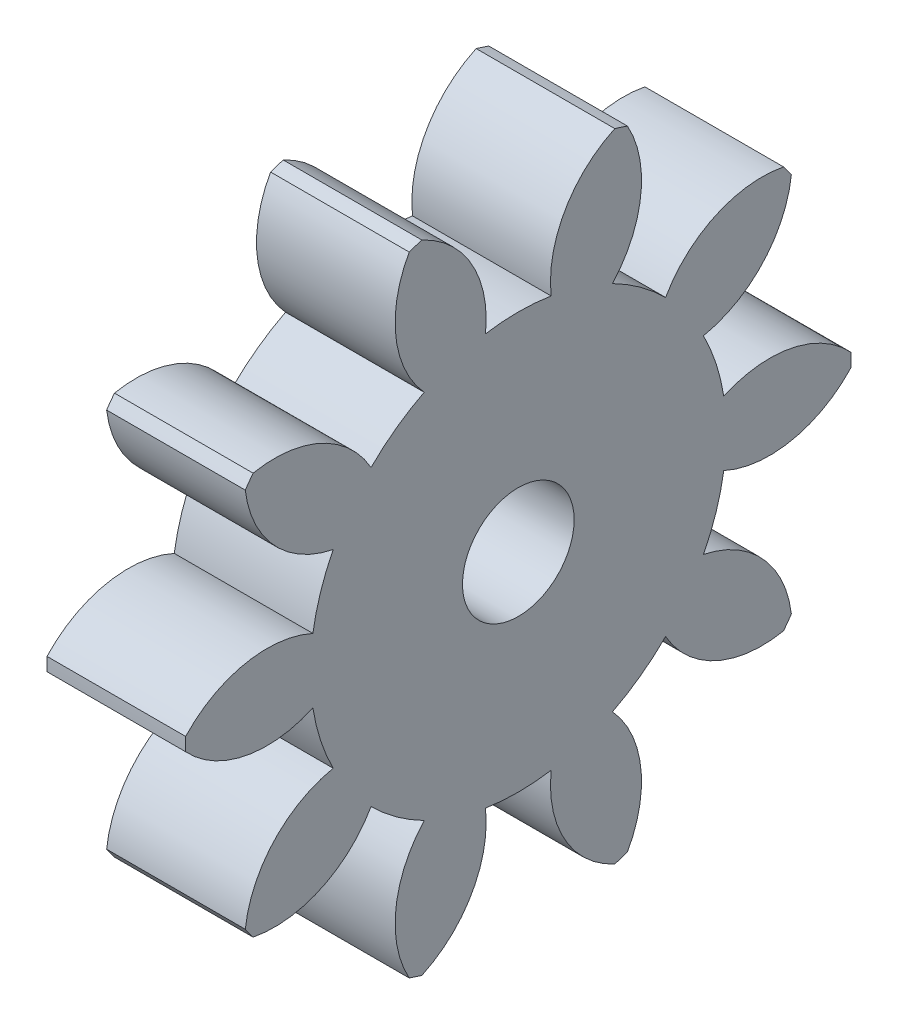
SolidWorks part; units mm, degrees
ref_plane "Plane1" through (0, 0, 0) normal (0, 0, 1) x (1, 0, 0)
ref_plane "Plane2" through (0, 0, 0) normal (0, 1, 0) x (1, 0, 0)
ref_plane "Plane3" through (0, 0, 0) normal (1, 0, 0) x (0, 0, -1)
other "Configuration Table"
sketch "HoldingSke" plane through (0, 0, 0) normal (0, 1, 0) x (1, 0, 0)
  line L0 (0, 0) -> (125.0706, -22.0533)
  line L1 (-15, 0) -> (100, 0) construction
  line L2 (0, 0) -> (-2.1039, 2.3779)
  line L3 (0, 0) -> (-11.863, 4.5341)
  line L4 (0, 0) -> (8.5048, 1.4996)
  line L5 (0, 0) -> (-47.5972, -17.7524)
  line L6 (0, 0) -> (-10.5278, -7.1032)
  line L7 (-2.1039, 2.3779) -> (8.8308, 51.9871)
  line L8 (-76.2, 54.61) -> (-75.184, 54.61)
  line L9 (-71.009, 38.7566) -> (-53.1078, 45.2721)
  line L10 (-76.2, 71.12) -> (104.1128, 71.12)
  line L11 (0, 0) -> (-12.7, 0)
  line L12 (-76.2, 101.6) -> (-76.0095, 101.6)
  line L13 (24.9733, 27.94) -> (52.9518, 28.4284)
  line L14 (24.9733, 27.94) -> (24.9746, 27.94)
  line L15 (24.9733, 27.94) -> (100.4006, 29.5858)
  circle A0 centre (0, 0) radius 0.3969
  circle A1 centre (0, 0) radius 19.0487
  circle A2 centre (0, 0) radius 38.1
  circle A3 centre (0, 0) radius 0.3969
  dimension "MHD" = 38.0975
  dimension "Hub_dia" = 76.2
  dimension "Bore" = 0.7937
  dimension "MBD" = 0.7937
  dimension "Num_teeth" = 10
  dimension "Pitch" = 127
  dimension "Overall_len" = 50.8
  dimension "Show_teeth" = 10
  dimension "Thickness" = 12.7
  dimension "OAL" = 50.8001
  dimension "T_dim" = 1.016
  dimension "Ap" = 20
  dimension "H" = 19.05
  dimension "Pitch_radius" = 180.3128
  dimension "Width" = 12.7
  dimension "Backlash" = 0.1905
  dimension "Addendum_fac" = 1
  dimension "Dedendum_fac" = 1.25
  dimension "Clearance_fac" = 0.25
  dimension "Dedendum_add" = 0.0013
sketch "BasProSke" plane through (0, 0, 0) normal (0, 1, 0) x (1, 0, 0)
  line L0 (-10, 0) -> (60, 0) construction
  line L1 (0, 0) -> (0, 30.48)
  line L2 (0, 0) -> (12.7, 0)
  line L3 (12.7, 0) -> (12.7, 30.48)
  line L4 (12.7, 30.48) -> (0, 30.48)
  dimension "Thickness" = 12.7
  dimension "Diameter" = 60.96
revolve "Base-Revolve" add sketch "BasProSke" angle 360 about L0
sketch "TooCutSke" plane through (0, 0, 0) normal (1, 0, 0) x (0, 0, -1)
  line L1 (0, 0) -> (0, 107) construction
  line L2 (0, 0) -> (-4.3061, 25.0323) construction
  line L3 (0, 0) -> (-15.536, 47.815) construction
  line L4 (-4.3061, 25.0323) -> (-7.768, 23.9075) construction
  arc A0 (3.0076, 18.8098) -> (-3.0076, 18.8098) centre (0, 0) ccw
  arc A1 (8.8722, 29.1867) -> (-8.8722, 29.1867) centre (0, 0) ccw
  circle A2 centre (0, 0) radius 25.4 construction
  circle A3 centre (0, 0) radius 23.8682 construction
  arc A4 (-3.0076, 18.8098) -> (-8.8722, 29.1867) centre (-13.1034, 19.9497) ccw
  arc A5 (8.8722, 29.1867) -> (3.0076, 18.8098) centre (13.1034, 19.9497) ccw
  dimension "Root_dia" = 38.0975
  dimension "Overcut_dia" = 61.0108
  dimension "Pitch_dia" = 50.8
  dimension "Base_dia" = 47.7364
  dimension "Flank_rad" = 10.16
  dimension "Half_ang" = 18
  dimension "Half_CT" = 3.6401
extrude "ToothCut" cut sketch "TooCutSke" along normal through all
fillet "Breaks" [suppressed] radius 0.1016
fillet "RootFillets" [suppressed] radius 1.2713
pattern_circular "TeethCuts" count 10 every 36 about axis through (-10, 0, 0) along (1, 0, 0) of "ToothCut", "RootFillets", "Breaks"
sketch "HubNeaOneSke" plane through (0, 0, 0) normal (-1, 0, 0) x (0, 0, 1)
  circle A0 centre (0, 0) radius 19.0487
  dimension "Diameter" = 38.0975
extrude "HubNearOne" [suppressed] add sketch "HubNeaOneSke" along normal blind 38.1001
sketch "HubNeaBotSke" plane through (0, 0, 0) normal (-1, 0, 0) x (0, 0, 1)
  circle A0 centre (0, 0) radius 19.0487
  dimension "Diameter" = 38.0975
extrude "HubNearBoth" [suppressed] add sketch "HubNeaBotSke" along normal blind 19.05
ref_plane "FarPln" through (12.7, 0, 0) normal (1, 0, 0) x (0, 0, -1)
sketch "HubFarSke" plane through (12.7, 0, 0) normal (1, 0, 0) x (0, 0, -1)
  circle A0 centre (0, 0) radius 19.0487
  dimension "Diameter" = 38.0975
extrude "HubFar" [suppressed] add sketch "HubFarSke" along normal blind 19.05
sketch "BorSke" plane through (0, 0, 0) normal (1, 0, 0) x (0, 0, -1)
  circle A0 centre (0, 0) radius 0.3969
  dimension "Diameter" = 0.7937
extrude "Bore" cut sketch "BorSke" along normal mid plane 101.6001
sketch "KeySke" plane through (0, 0, 0) normal (1, 0, 0) x (0, 0, -1)
  line L0 (-0.127, 0) -> (-0.127, 0.6191)
  line L1 (-0.127, 0.6191) -> (0.127, 0.6191)
  line L2 (0.127, 0.6191) -> (0.127, 0)
  line L3 (0, 0) -> (0, 34) construction
  line L4 (-0.127, 0) -> (0.127, 0)
  dimension "Offset" = 0.6191
extrude "Keyway" [suppressed] cut sketch "KeySke" along normal mid plane 101.6001
pattern_circular "Keyway2" [suppressed] count 2 every 90 about axis through (-10, 0, 0) along (1, 0, 0)
sketch "Sketch1" plane through (12.7, 0, 0) normal (1, 0, 0) x (0, 0, -1)
  circle A0 centre (0, 0) radius 5.1137
extrude "Cut-Extrude1" cut sketch "Sketch1" against normal through all
equation "' \"Pitch@HoldingSke\" = 4"
equation "' \"Num_teeth@HoldingSke\" = 12"
equation "' \"Ap@HoldingSke\" =  20"
equation "' \"Ap@HoldingSke\" = 20"
equation "' \"Width@HoldingSke\" = 0.5"
equation "' \"Hub_dia@HoldingSke\"= 1"
equation "' \"Hub_dia@HoldingSke\" = 1"
equation "' \"Overall_len@HoldingSke\" = 1.0"
equation "' \"Bore@HoldingSke\" = 0.75"
equation "' \"T_dim@HoldingSke\" = 0.85"
equation "' \"Width@KeySke\" = 0.25"
equation "' \"Show_teeth@HoldingSke\" = 13"
equation "' \"Backlash@HoldingSke\" = 0.009"
equation "' \"Addendum_fac@HoldingSke\" = 1.0"
equation "' \"Dedendum_fac@HoldingSke\" = 1.25"
equation "' \"Dedendum_add@HoldingSke\" = 0.00005"
equation "' \"Clearance_fac@HoldingSke\" = 0.25"
equation "' \"Pitch@HoldingSke\" = 0.5"
equation "' \"Num_teeth@HoldingSke\" = 23"
equation "' \"Show_teeth@HoldingSke\" = 23"
equation "' \"Backlash@HoldingSke\" = 0.0375"
equation "\"Overcut_dia@TooCutSke\" = (\"Num_teeth@HoldingSke\" + 2 * \"Addendum_fac@HoldingSke\") / \"Pitch@HoldingSke\" + 0.002"
equation "\"Pitch_dia@TooCutSke\" = \"Num_teeth@HoldingSke\" / \"Pitch@HoldingSke\""
equation "\"Base_dia@TooCutSke\" = \"Num_teeth@HoldingSke\" / \"Pitch@HoldingSke\" * cos((\"Ap@HoldingSke\"  * 3.14159265 / 180))"
equation "\"Root_dia@TooCutSke\" = (\"Num_teeth@HoldingSke\" + 2) / \"Pitch@HoldingSke\" - 2 * (\"Addendum_fac@HoldingSke\" + \"Dedendum_fac@HoldingSke\") / \"Pitch@HoldingSke\" - \"Dedendum_add@HoldingSke\" * 2"
equation "\"Half_ang@TooCutSke\" = 180 / \"Num_teeth@HoldingSke\""
equation "\"Half_CT@TooCutSke\" = \"Num_teeth@HoldingSke\" / \"Pitch@HoldingSke\" * sin((3.14159265 / 2 / \"Num_teeth@HoldingSke\")) / 2 - 7 * \"Backlash@HoldingSke\" / 4"
equation "\"Flank_rad@TooCutSke\" = \"Num_teeth@HoldingSke\" / \"Pitch@HoldingSke\" / 5"
equation "\"Radius@RootFillets\" = \"Clearance_fac@HoldingSke\" / \"Pitch@HoldingSke\" + \"Dedendum_add@HoldingSke\""
equation "\"Break_rad@Breaks\" = 0.02 / \"Pitch@HoldingSke\""
equation "\"Thickness@HoldingSke\" = \"Width@HoldingSke\""
equation "\"OAL@HoldingSke\" = \"Thickness@HoldingSke\""
equation "\"MHD@HoldingSke\" = (\"Num_teeth@HoldingSke\" + 2) / \"Pitch@HoldingSke\" - 2 * (\"Addendum_fac@HoldingSke\" + \"Dedendum_fac@HoldingSke\")  / \"Pitch@HoldingSke\" - \"Dedendum_add@HoldingSke\" * 2"
equation "\"MBD@HoldingSke\" = (\"Num_teeth@HoldingSke\" + 2) / \"Pitch@HoldingSke\" - 2 * (\"Addendum_fac@HoldingSke\" + \"Dedendum_fac@HoldingSke\")  / \"Pitch@HoldingSke\" - \"Dedendum_add@HoldingSke\" * 2 - 0.002"
equation "\"MHD@HoldingSke\" = ((sgn( \"MHD@HoldingSke\" - \"Hub_dia@HoldingSke\" )-1)*( \"MHD@HoldingSke\" - \"Hub_dia@HoldingSke\" ))/-2+ \"Hub_dia@HoldingSke\""
equation "\"MBD@HoldingSke\" = ((sgn( \"MBD@HoldingSke\" - \"Bore@HoldingSke\" )-1)*( \"MBD@HoldingSke\" - \"Bore@HoldingSke\" ))/-2+ \"Bore@HoldingSke\""
equation "\"OAL@HoldingSke\" = ((sgn( \"OAL@HoldingSke\" - \"Overall_len@HoldingSke\" )+1)*( \"OAL@HoldingSke\" - \"Overall_len@HoldingSke\" ))/2 + \"Overall_len@HoldingSke\" + 0.000002"
equation "\"Num_teeth@TeethCuts\" = int( \"Show_teeth@HoldingSke\" ) + 1"
equation "\"Num_teeth@TeethCuts\" = ((sgn( \"Num_teeth@TeethCuts\" - \"Num_teeth@HoldingSke\" )-1)*( \"Num_teeth@TeethCuts\" - \"Num_teeth@HoldingSke\" ))/-2+ \"Num_teeth@HoldingSke\""
equation "\"Num_teeth@TeethCuts\" = ((sgn( \"Num_teeth@TeethCuts\" - 2.0)+1)*( \"Num_teeth@TeethCuts\" - 2.0))/2 +2.0"
equation "\"Angle@TeethCuts\" = 360.0 / \"Num_teeth@HoldingSke\""
equation "\"Diameter@BasProSke\" = (\"Num_teeth@HoldingSke\" + 2 * \"Addendum_fac@HoldingSke\") / \"Pitch@HoldingSke\""
equation "\"Thickness@BasProSke\"  = \"Thickness@HoldingSke\""
equation "' \"Fillet_rad@BasProSke\" =  \"Thickness@HoldingSke\" * 0.05"
equation "' \"Fillet_rad@BasProSke\" = \"Thickness@HoldingSke\" * 0.05"
equation "\"MHD@HoldingSke\" = ((sgn( \"MHD@HoldingSke\" - \"Root_dia@TooCutSke\" )-1)*( \"MHD@HoldingSke\" - \"Root_dia@TooCutSke\" ))/-2+ \"Root_dia@TooCutSke\""
equation "\"Diameter@HubNeaOneSke\" = \"MHD@HoldingSke\""
equation "\"Length@HubNearOne\" = \"OAL@HoldingSke\" - \"Thickness@BasProSke\""
equation "\"Diameter@HubNeaBotSke\" = \"MHD@HoldingSke\""
equation "\"Length@HubNearBoth\" = ( \"OAL@HoldingSke\" - \"Thickness@BasProSke\" ) / 2.0"
equation "\"Thickness@FarPln\" = \"Thickness@BasProSke\""
equation "\"Diameter@HubFarSke\" = \"MHD@HoldingSke\""
equation "\"Length@HubFar\" = ( \"OAL@HoldingSke\" - \"Thickness@BasProSke\" ) / 2.0"
equation "\"Diameter@BorSke\" = \"MBD@HoldingSke\""
equation "\"D1@Bore\" = \"OAL@HoldingSke\" * 2.0"
equation "\"D1@Keyway\" = \"OAL@HoldingSke\" * 2.0"
equation "\"Offset@KeySke\" = \"T_dim@HoldingSke\" - \"MBD@HoldingSke\" / 2.0"
